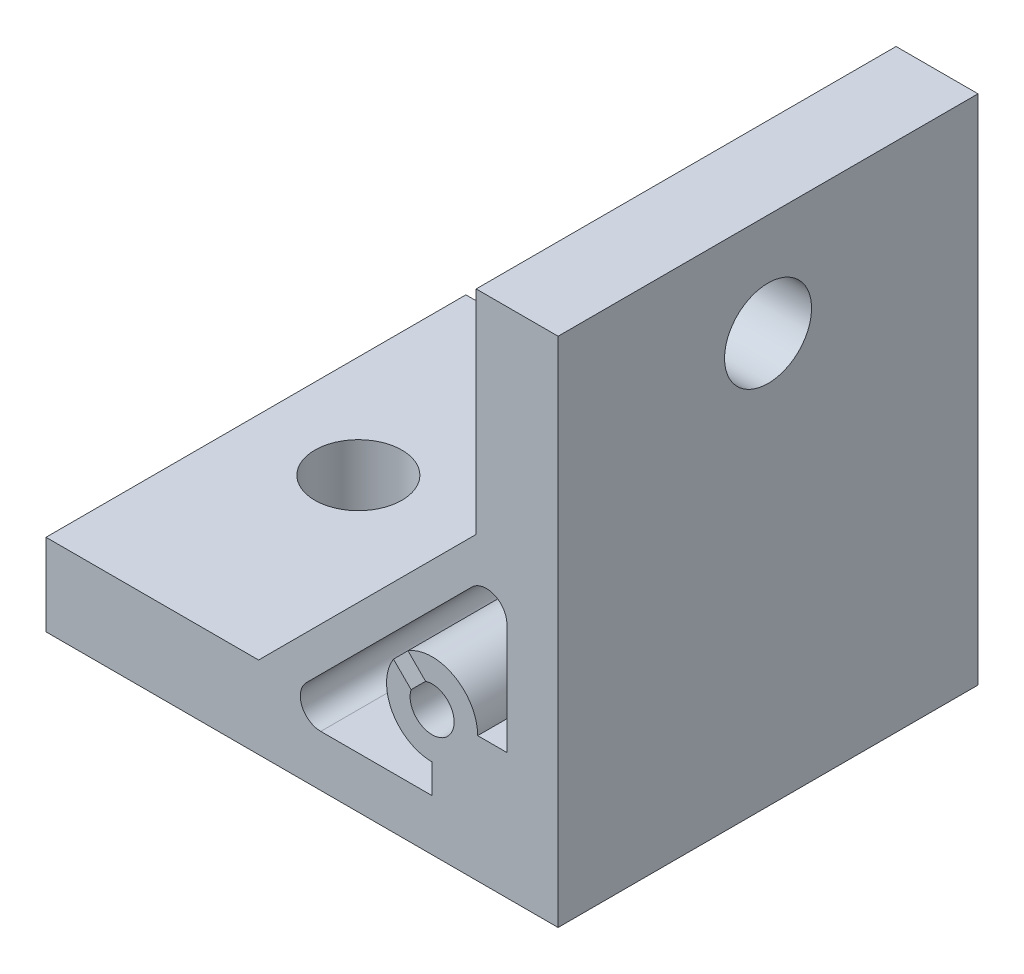
SolidWorks part; units mm, degrees
ref_plane "前视基准面" through (0, 0, 0) normal (0, 0, 1) x (1, 0, 0)
ref_plane "上视基准面" through (0, 0, 0) normal (0, 1, 0) x (1, 0, 0)
ref_plane "右视基准面" through (0, 0, 0) normal (1, 0, 0) x (0, 0, -1)
sketch "草图1" plane through (0, 0, 0) normal (0, 0, 1) x (1, 0, 0)
  line B0 (0, 0) -> (50, 0)
  line B1 (50, 0) -> (50, 50)
  line B2 (0, 8) -> (20.7574, 8)
  line B3 (42, 29.2426) -> (42, 50)
  line B4 (0, 8) -> (0, 0)
  line B5 (42, 50) -> (50, 50)
  line B6 (37.0613, 14.3529) -> (35.341, 16.0733)
  line B7 (35.6471, 12.9387) -> (33.9267, 14.659)
  line B8 (25.4142, 8.4142) -> (41.5858, 24.5858)
  line B9 (20.7574, 8) -> (42, 29.2426)
  line B10 (26.8284, 5) -> (37.7, 5)
  line B11 (45, 23.1716) -> (45, 12.3)
  line B12 (37.7, 5) -> (37.7, 7.85)
  line B13 (42.15, 12.3) -> (45, 12.3)
  arc B14 (33.9267, 14.659) -> (37.7, 7.85) centre (37.7, 12.3) ccw
  arc B15 (42.15, 12.3) -> (35.341, 16.0733) centre (37.7, 12.3) ccw
  arc B16 (35.6471, 12.9387) -> (37.0613, 14.3529) centre (37.7, 12.3) ccw
  arc B17 (25.4142, 8.4142) -> (26.8284, 5) centre (26.8284, 7) ccw
  arc B18 (45, 23.1716) -> (41.5858, 24.5858) centre (43, 23.1716) ccw
sketch_block_instance "A$C19004297-1"
sketch_block "A$C19004297"
extrude "凸台-拉伸1" add sketch "草图1" along normal mid plane 41
sketch "草图3" plane through (0, 8, 0) normal (0, 1, 0) x (1, 0, 0)
  line L0 (0, -20.5) -> (0, 20.5) construction
  circle A0 centre (10, 0) radius 4.25
  dimension "D1" = 10
extrude "切除-拉伸1" cut sketch "草图3" against normal through all
sketch "草图4" plane through (6.3787, -6.3787, 0) normal (-0.7071, 0.7071, 0) x (0, 0, 1)
  line L0 (20.5, 35.3553) -> (-20.5, 35.3553) construction
  line L2 (20.5, 50.3762) -> (20.5, 20.3345) construction
  line L3 (-20.5, 50.3762) -> (-20.5, 20.3345) construction
ref_plane "基准面2" through (25, 25, 0) normal (-0.7071, -0.7071, 0) x (0, 0, 1)
mirror "镜向1" about plane through (25, 25, 0) normal (-0.7071, -0.7071, 0) of "切除-拉伸1"
